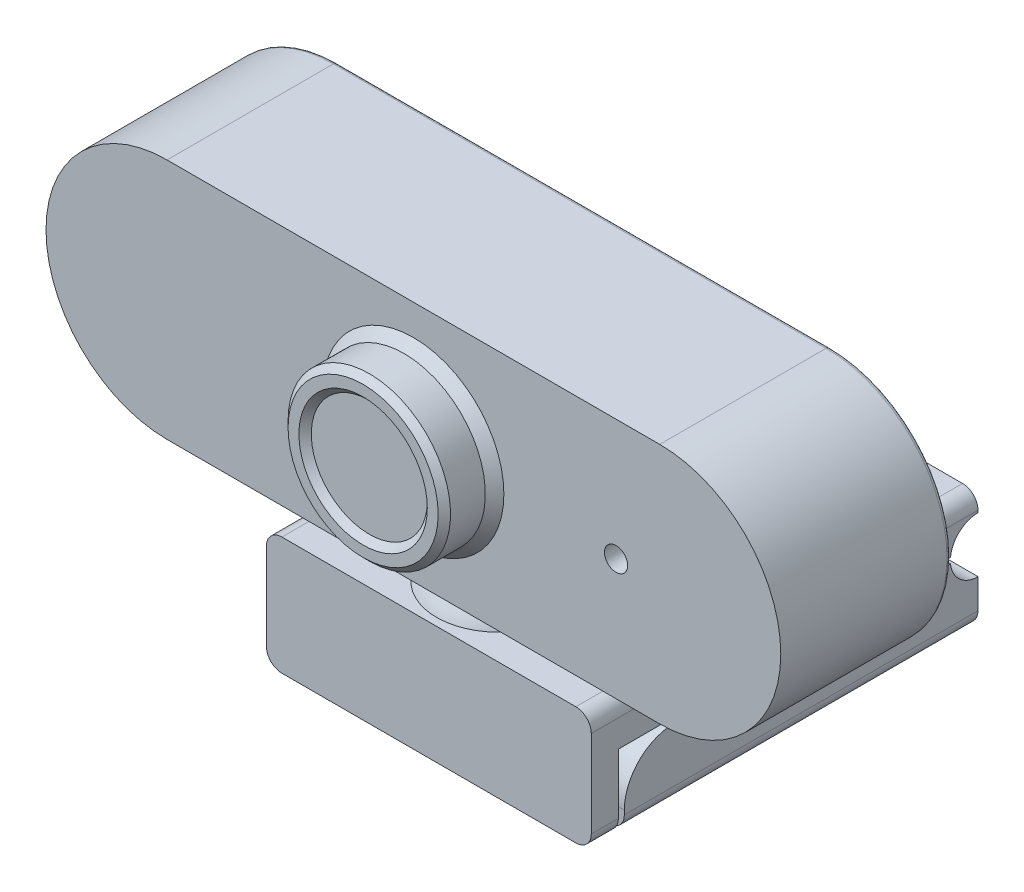
SolidWorks part; units mm, degrees
ref_plane "Plano frontal" through (0, 0, 0) normal (0, 0, 1) x (1, 0, 0)
ref_plane "Plano superior" through (0, 0, 0) normal (0, 1, 0) x (1, 0, 0)
ref_plane "Plano direito" through (0, 0, 0) normal (1, 0, 0) x (0, 0, -1)
sketch "Esboço1" plane through (0, 0, 0) normal (0, 0, 1) x (1, 0, 0)
  line L0 (-31.85, 0) -> (31.85, 0) construction
  line L1 (-31.85, 15.65) -> (31.85, 15.65)
  line L2 (-31.85, -15.65) -> (31.85, -15.65)
  line L3 (0, 0) -> (0, 24.8854) construction
  line L4 (0, 24.8854) -> (-47.5, 24.8854) construction
  line L5 (-47.5, 24.8854) -> (-47.5, -9.4337) construction
  arc A0 (-31.85, 15.65) -> (-31.85, -15.65) centre (-31.85, 0) ccw
  arc A1 (31.85, -15.65) -> (31.85, 15.65) centre (31.85, 0) ccw
  point P3 (0, 0)
  dimension "D1" = 47.5
  dimension "D2" = 31.3
extrude "Ressalto-extrusão1" add sketch "Esboço1" along normal blind 22
sketch "Esboço2" plane through (0, 0, 22) normal (0, 0, 1) x (1, 0, 0)
  circle A0 centre (0, 0) radius 10.5
  circle A1 centre (0, 0) radius 7.5
  dimension "D1" = 21
  dimension "D2" = 3
extrude "Ressalto-extrusão2" add sketch "Esboço2" along normal blind 6.5
chamfer "Chanfro1" distance 0.8 angle 45 2 edges at (7.5, 0, 28.5) (10.5, 0, 28.5)
chamfer "Chanfro2" distance 1.2 angle 45 1 edges at (10.5, 0, 22)
ref_plane "Plano1" through (0, 0, 27.7) normal (0, 0, 1) x (1, 0, 0)
sketch "Esboço3" plane through (0, 0, 27.7) normal (0, 0, 1) x (1, 0, 0)
  circle A0 centre (0, 0) radius 7.5 construction
  circle A1 centre (0, 0) radius 7.5
extrude "Ressalto-extrusão3" add sketch "Esboço3" against normal blind 1
sketch "Esboço4" plane through (0, 0, 22) normal (0, 0, 1) x (1, 0, 0)
  line L0 (11.7, 0) -> (11.7, 9.2038) construction
  circle A0 centre (26.2, 0) radius 1.5
  circle A1 centre (0, 0) radius 11.7 construction
  dimension "D2" = 3
  dimension "D1" = 14.5
extrude "Corte-extrusão1" cut sketch "Esboço4" against normal blind 18
sketch "Esboço5" plane through (0, -15.65, 0) normal (0, -1, 0) x (1, 0, 0)
  line L0 (0, 22) -> (0, 0) construction
  line L3 (-31.85, 22) -> (31.85, 22) construction
  circle A0 centre (0, 11) radius 8
  point P5 (0, 11)
  dimension "D1" = 16
extrude "Ressalto-extrusão4" add sketch "Esboço5" along normal blind 3
fillet "Filete2" radius 0.5 6 edges at (-47.5, 0, 0) (0, 15.65, 0) (47.5, 0, 0) (0, -18.65, 3) (0, -15.65, 19) (0, -15.65, 0)
ref_plane "Plano2" through (0, -21.15, 0) normal (0, -1, 0) x (-1, 0, 0)
sketch "Esboço6" plane through (0, -21.15, 0) normal (0, -1, 0) x (-1, 0, 0)
  line L0 (31.85, -22) -> (-31.85, -22) construction
  line L1 (21, -20) -> (-21, -20)
  line L2 (21, -20) -> (21, 30)
  line L3 (21, 30) -> (-21, 30)
  line L4 (-21, -20) -> (-21, 30)
  line L5 (21, -20) -> (-21, 30) construction
  line L6 (21, 30) -> (-21, -20) construction
  line L7 (0, 0) -> (0, 23.2015) construction
  point P0 (0, 5)
  dimension "D1" = 42
  dimension "D2" = 50
  dimension "D3" = 2
extrude "Ressalto-extrusão5" add sketch "Esboço6" along normal blind 15.25 separate body
fillet "Filete3" radius 2 4 edges at (21, -36.4, -5) (-21, -36.4, -5) (21, -21.15, -5) (-21, -21.15, -5)
sketch "Esboço7" plane through (-21, 0, 0) normal (-1, 0, 0) x (0, 0, 1)
  line L0 (-30, -26.65) -> (16.5, -26.65)
  line L1 (16.5, -26.65) -> (16.5, -38.0467)
  line L2 (-30, -21.15) -> (20, -21.15) construction
  line L3 (20, -34.4) -> (20, -23.15) construction
  line L4 (-30, -26.65) -> (-31.6167, -26.65)
  line L5 (-30, -34.4) -> (-30, -23.15) construction
  line L6 (-30, -27.3624) -> (9.2304, -27.3624)
  line L7 (15.7304, -33.8624) -> (15.7304, -38.0467)
  line L8 (-30, -27.3624) -> (-31.6167, -27.3624)
  line L11 (15.7304, -38.0467) -> (16.5, -38.0467)
  line L12 (-31.6167, -26.65) -> (-31.6167, -27.3624)
  arc A0 (9.2304, -27.3624) -> (15.7304, -33.8624) centre (9.2304, -33.8624) cw
  dimension "D3" = 6.5
  dimension "D1" = 5.5
  dimension "D2" = 3.5
extrude "Corte-extrusão2" cut sketch "Esboço7" against normal blind 70.25 and the other way blind 19
sketch "Esboço8" plane through (0, 0, 0) normal (1, 0, 0) x (0, 0, -1)
  line L0 (30, -26.65) -> (30, -27.3624) construction
  circle A0 centre (30, -27.0062) radius 3.575
  dimension "D1" = 7.15
extrude "Corte-extrusão3" cut sketch "Esboço8" against normal blind 34.25 and the other way blind 36
sketch "Esboço9" plane through (0, 0, 0) normal (1, 0, 0) x (0, 0, -1)
  circle A0 centre (30, -27.0062) radius 3.575
extrude "Ressalto-extrusão6" add sketch "Esboço9" along normal mid plane 21.7
sketch "Esboço10" plane through (0, -36.4, 0) normal (0, -1, 0) x (1, 0, 0)
  line L0 (0, 15.7304) -> (0, -30) construction
  line L1 (19, 15.7304) -> (-19, 15.7304) construction
  line L2 (10.85, -30) -> (-10.85, -30) construction
  circle A0 centre (0, -7.1348) radius 3.5
  dimension "D1" = 7
extrude "Corte-extrusão4" cut sketch "Esboço10" against normal blind 5.7
sketch "Esboço11" plane through (0, -18.65, 0) normal (0, -1, 0) x (1, 0, 0)
  point P0 (0, 11)
ref_plane "Plano3" through (0, 0, 11) normal (0, 0, 1) x (1, 0, 0)
sketch "Esboço12" plane through (0, 0, 11) normal (0, 0, 1) x (1, 0, 0)
  line L0 (-8, -21.15) -> (-8, -18.65) construction
  line L1 (19, -21.15) -> (-19, -21.15) construction
  line L2 (-7.5, -18.65) -> (7.5, -18.65) construction
  line L3 (-8, -18.65) -> (0, -18.65) construction
  line L5 (-8, -16.15) -> (-8, -18.15) construction
  line L7 (0, -15.65) -> (0, -21.15)
  line L8 (0, -21.15) -> (-8, -21.15)
  arc A0 (-8, -21.15) -> (0, -15.65) centre (0, -24.2182) cw
  dimension "D1" = 0
revolve "Revolução1" add sketch "Esboço12" angle 360 about L7
sketch "Esboço13" plane through (0, 0, 0) normal (0, 0, -1) x (-1, 0, 0)
  line L0 (31.85, -15.65) -> (-31.85, -15.65) construction
  circle A0 centre (-26.85, -7.65) radius 2
  arc A1 (-31.85, 15.65) -> (-31.85, -15.65) centre (-31.85, 0) ccw construction
  dimension "D1" = 4
  dimension "D2" = 8
  dimension "D3" = 5
extrude "Ressalto-extrusão7" add sketch "Esboço13" along normal blind 10
sketch "Esboço14" plane through (0, 0, 22) normal (0, 0, 1) x (1, 0, 0)
  point P0 (0, 0)
  point P1 (-55.0368, 12.878)
ref_plane "Plano4" through (0, 0, 0) normal (0, 1, 0) x (1, 0, 0)
sketch "Esboço15" plane through (0, 0, 0) normal (0, 1, 0) x (1, 0, 0)
  line L3 (-150, -172) -> (0, -22) construction
  line L4 (0, -22) -> (150, -172) construction
